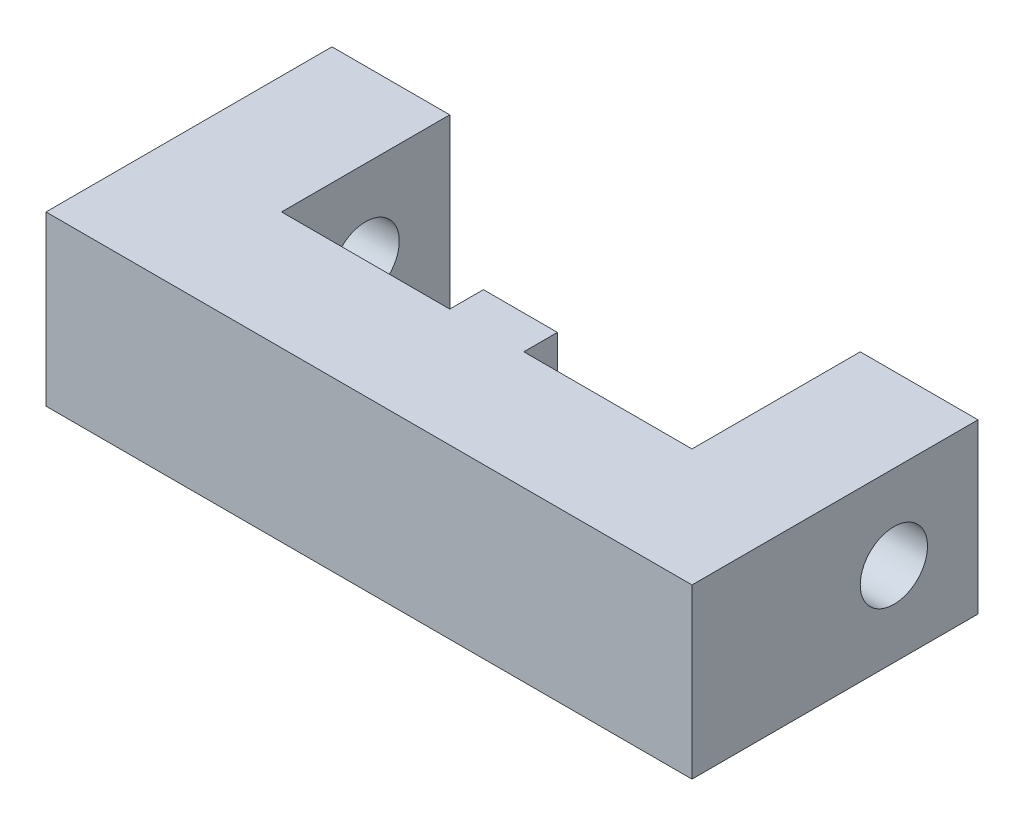
SolidWorks part; units mm, degrees
ref_plane "Front Plane" through (0, 0, 0) normal (0, 0, 1) x (1, 0, 0)
ref_plane "Top Plane" through (0, 0, 0) normal (0, 1, 0) x (1, 0, 0)
ref_plane "Right Plane" through (0, 0, 0) normal (1, 0, 0) x (0, 0, -1)
sketch "Sketch1" plane through (0, 0, 0) normal (0, 1, 0) x (1, 0, 0)
  line L0 (0, 0) -> (24.384, 0)
  line L1 (21.59, 8.89) -> (21.59, 11.43)
  line L2 (21.59, 11.43) -> (24.384, 11.43)
  line L3 (0, 0) -> (0, 21.59)
  line L4 (0, 21.59) -> (8.89, 21.59)
  line L5 (8.89, 21.59) -> (8.89, 8.89)
  line L6 (8.89, 8.89) -> (21.59, 8.89)
  line L7 (24.384, 11.43) -> (24.384, 0)
  dimension "D1" = 2.794
  dimension "D2" = 12.7
  dimension "D3" = 8.89
  dimension "D4" = 8.89
  dimension "D5" = 12.7
  dimension "D6" = 2.54
extrude "Boss-Extrude1" add sketch "Sketch1" along normal blind 12.7
mirror "Mirror1" about plane through (24.384, 12.7, -11.43) normal (-1, 0, 0) of "Boss-Extrude1"
sketch "Sketch3" plane through (0, 0, 0) normal (-1, 0, 0) x (0, 0, 1)
  line L0 (-21.59, 6.35) -> (0, 6.35) construction
  line L1 (-21.59, 12.7) -> (-21.59, 0) construction
  circle A0 centre (-15.24, 6.35) radius 2.54
  dimension "D1" = 5.08
  dimension "D2" = 6.35
extrude "Cut-Extrude1" cut sketch "Sketch3" against normal through all both and the other way through all
